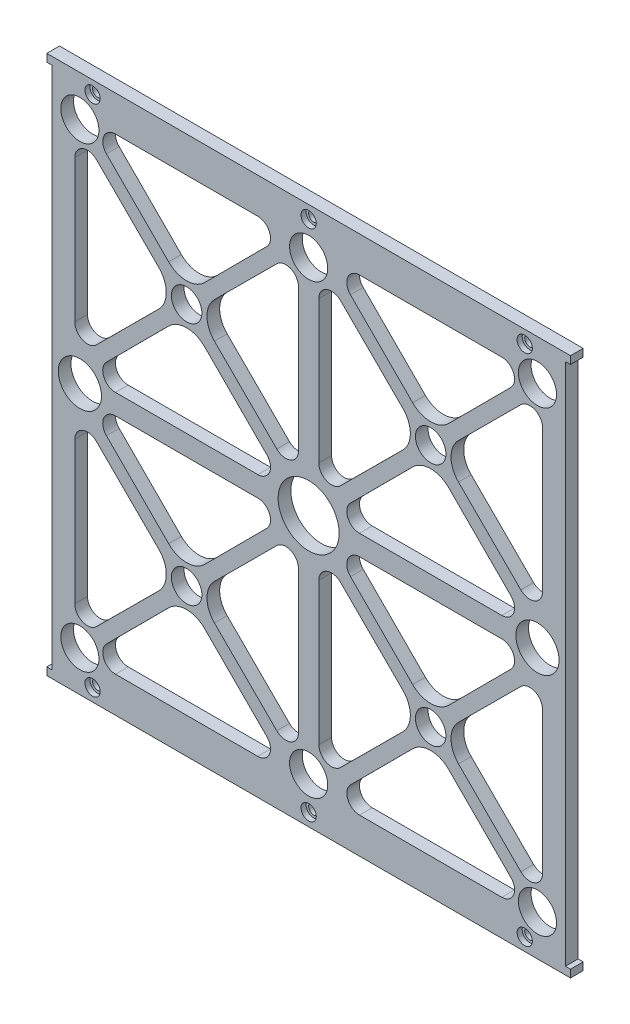
SolidWorks part; units mm, degrees
ref_plane "Přední rovina" through (0, 0, 0) normal (0, 0, 1) x (1, 0, 0)
ref_plane "Horní rovina" through (0, 0, 0) normal (0, 1, 0) x (1, 0, 0)
ref_plane "Pravá rovina" through (0, 0, 0) normal (1, 0, 0) x (0, 0, -1)
sketch "Skica1" plane through (0, 0, 0) normal (0, 0, 1) x (1, 0, 0)
  line L0 (0, 0) -> (103, 0) construction
  line L1 (0, 0) -> (0, 106) construction
  line L7 (103, 0) -> (103, 106) construction
  line L19 (-103, 106) -> (103, 106)
  line L20 (103, 106) -> (103, 103)
  line L21 (103, 103) -> (101, 103)
  line L22 (101, 103) -> (101, -103)
  line L23 (103, -103) -> (101, -103)
  line L24 (103, -106) -> (103, -103)
  line L25 (-103, -106) -> (103, -106)
  line L26 (-103, 103) -> (-101, 103)
  line L27 (-103, 106) -> (-103, 103)
  line L28 (-101, 103) -> (-101, -103)
  line L29 (-103, -103) -> (-101, -103)
  line L30 (-103, -106) -> (-103, -103)
  dimension "D1" = 212
  dimension "D2" = 206
  dimension "D3" = 3
  dimension "D4" = 2
extrude "Přidat vysunutím1" add sketch "Skica1" along normal blind 5 contours L27 L26 L28 L29 L30 L25 L24 L23 L22 L21 L20 L19
sketch "Skica2" plane through (0, 0, 5) normal (0, 0, 1) x (1, 0, 0)
  line L0 (0, 0) -> (0, 101) construction
  line L1 (0, 101) -> (-85, 101) construction
  line L2 (0, 0) -> (-79.6692, 0) construction
  circle A6 centre (-85, 101) radius 2
  circle A7 centre (0, 101) radius 2
  circle A8 centre (85, 101) radius 2
  circle A9 centre (-85, -101) radius 2
  circle A10 centre (0, -101) radius 2
  circle A11 centre (85, -101) radius 2
  dimension "D1" = 85
  dimension "D4" = 3
  dimension "D5" = 85
  dimension "D3" = 4
  dimension "D2" = 101
extrude "Odebrat vysunutím1" cut sketch "Skica2" against normal through all
sketch "Skica4" plane through (0, 0, 5) normal (0, 0, 1) x (1, 0, 0)
  line L0 (0, 0) -> (48, 0) construction
  line L1 (48, 0) -> (48, 48) construction
  line L2 (48, 48) -> (48, 66) construction
  line L3 (48, 66) -> (48, 87) construction
  line L4 (48, 87) -> (20, 87) construction
  line L5 (40.9187, 58.9392) -> (16.4593, 83.4696)
  line L6 (55.0813, 58.9392) -> (79.5407, 83.4696)
  line L7 (20, 92) -> (76, 92)
  line L8 (48, 48) -> (-1, 97) construction
  line L10 (37.0608, 55.0813) -> (12.5304, 79.5407)
  line L11 (4, 76) -> (4, 20)
  line L12 (37.0608, 40.9187) -> (12.5304, 16.4593)
  line L13 (58.9392, 40.9187) -> (83.4696, 16.4593)
  line L14 (92, 76) -> (92, 20)
  line L15 (58.9392, 55.0813) -> (83.4696, 79.5407)
  line L16 (48, 48) -> (66, 48) construction
  line L20 (40.9187, 37.0608) -> (16.4593, 12.5304)
  line L21 (20, 4) -> (76, 4)
  line L22 (55.0813, 37.0608) -> (79.5407, 12.5304)
  line L23 (0, 0) -> (0, 95) construction
  line L24 (-40.9187, 58.9392) -> (-16.4593, 83.4696)
  line L25 (-20, 92) -> (-76, 92)
  line L26 (-55.0813, 58.9392) -> (-79.5407, 83.4696)
  line L27 (-58.9392, 55.0813) -> (-83.4696, 79.5407)
  line L28 (-92, 76) -> (-92, 20)
  line L29 (-58.9392, 40.9187) -> (-83.4696, 16.4593)
  line L30 (-55.0813, 37.0608) -> (-79.5407, 12.5304)
  line L31 (-20, 4) -> (-76, 4)
  line L32 (-40.9187, 37.0608) -> (-16.4593, 12.5304)
  line L33 (-37.0608, 40.9187) -> (-12.5304, 16.4593)
  line L34 (-4, 76) -> (-4, 20)
  line L35 (-37.0608, 55.0813) -> (-12.5304, 79.5407)
  line L36 (40.9187, -58.9392) -> (16.4593, -83.4696)
  line L37 (20, -92) -> (76, -92)
  line L38 (55.0813, -58.9392) -> (79.5407, -83.4696)
  line L39 (58.9392, -55.0813) -> (83.4696, -79.5407)
  line L40 (92, -76) -> (92, -20)
  line L41 (58.9392, -40.9187) -> (83.4696, -16.4593)
  line L42 (55.0813, -37.0608) -> (79.5407, -12.5304)
  line L43 (20, -4) -> (76, -4)
  line L44 (40.9187, -37.0608) -> (16.4593, -12.5304)
  line L45 (37.0608, -40.9187) -> (12.5304, -16.4593)
  line L46 (4, -76) -> (4, -20)
  line L47 (37.0608, -55.0813) -> (12.5304, -79.5407)
  line L48 (-37.0608, -55.0813) -> (-12.5304, -79.5407)
  line L49 (-4, -76) -> (-4, -20)
  line L50 (-37.0608, -40.9187) -> (-12.5304, -16.4593)
  line L51 (-55.0813, -58.9392) -> (-79.5407, -83.4696)
  line L52 (-20, -92) -> (-76, -92)
  line L53 (-40.9187, -58.9392) -> (-16.4593, -83.4696)
  line L54 (-58.9392, -40.9187) -> (-83.4696, -16.4593)
  line L55 (-92, -76) -> (-92, -20)
  line L56 (-58.9392, -55.0813) -> (-83.4696, -79.5407)
  line L57 (-40.9187, -37.0608) -> (-16.4593, -12.5304)
  line L58 (-20, -4) -> (-76, -4)
  line L59 (-55.0813, -37.0608) -> (-79.5407, -12.5304)
  circle A0 centre (48, 48) radius 6
  arc A1 (40.9187, 58.9392) -> (55.0813, 58.9392) centre (48, 66) ccw
  arc A2 (20, 92) -> (16.4593, 83.4696) centre (20, 87) ccw
  arc A3 (76, 92) -> (79.5407, 83.4696) centre (76, 87) cw
  arc A4 (4, 76) -> (12.5304, 79.5407) centre (9, 76) cw
  arc A5 (4, 20) -> (12.5304, 16.4593) centre (9, 20) ccw
  arc A6 (37.0608, 55.0813) -> (37.0608, 40.9187) centre (30, 48) cw
  arc A7 (58.9392, 55.0813) -> (58.9392, 40.9187) centre (66, 48) ccw
  arc A8 (92, 20) -> (83.4696, 16.4593) centre (87, 20) cw
  arc A9 (92, 76) -> (83.4696, 79.5407) centre (87, 76) ccw
  arc A10 (20, 4) -> (16.4593, 12.5304) centre (20, 9) cw
  arc A11 (76, 4) -> (79.5407, 12.5304) centre (76, 9) ccw
  arc A12 (40.9187, 37.0608) -> (55.0813, 37.0608) centre (48, 30) cw
  arc A13 (-20, 92) -> (-16.4593, 83.4696) centre (-20, 87) cw
  arc A14 (-76, 92) -> (-79.5407, 83.4696) centre (-76, 87) ccw
  arc A15 (-40.9187, 58.9392) -> (-55.0813, 58.9392) centre (-48, 66) cw
  circle A16 centre (-48, 48) radius 6
  arc A17 (-92, 76) -> (-83.4696, 79.5407) centre (-87, 76) cw
  arc A18 (-92, 20) -> (-83.4696, 16.4593) centre (-87, 20) ccw
  arc A19 (-58.9392, 55.0813) -> (-58.9392, 40.9187) centre (-66, 48) cw
  arc A20 (-40.9187, 37.0608) -> (-55.0813, 37.0608) centre (-48, 30) ccw
  arc A21 (-76, 4) -> (-79.5407, 12.5304) centre (-76, 9) cw
  arc A22 (-20, 4) -> (-16.4593, 12.5304) centre (-20, 9) ccw
  arc A23 (-37.0608, 55.0813) -> (-37.0608, 40.9187) centre (-30, 48) ccw
  arc A24 (-4, 20) -> (-12.5304, 16.4593) centre (-9, 20) cw
  arc A25 (-4, 76) -> (-12.5304, 79.5407) centre (-9, 76) ccw
  arc A26 (20, -92) -> (16.4593, -83.4696) centre (20, -87) cw
  arc A27 (76, -92) -> (79.5407, -83.4696) centre (76, -87) ccw
  arc A28 (40.9187, -58.9392) -> (55.0813, -58.9392) centre (48, -66) cw
  circle A29 centre (48, -48) radius 6
  arc A30 (92, -76) -> (83.4696, -79.5407) centre (87, -76) cw
  arc A31 (92, -20) -> (83.4696, -16.4593) centre (87, -20) ccw
  arc A32 (58.9392, -55.0813) -> (58.9392, -40.9187) centre (66, -48) cw
  arc A33 (40.9187, -37.0608) -> (55.0813, -37.0608) centre (48, -30) ccw
  arc A34 (76, -4) -> (79.5407, -12.5304) centre (76, -9) cw
  arc A35 (20, -4) -> (16.4593, -12.5304) centre (20, -9) ccw
  arc A36 (37.0608, -55.0813) -> (37.0608, -40.9187) centre (30, -48) ccw
  arc A37 (4, -20) -> (12.5304, -16.4593) centre (9, -20) cw
  arc A38 (4, -76) -> (12.5304, -79.5407) centre (9, -76) ccw
  arc A39 (-4, -76) -> (-12.5304, -79.5407) centre (-9, -76) cw
  arc A40 (-4, -20) -> (-12.5304, -16.4593) centre (-9, -20) ccw
  arc A41 (-37.0608, -55.0813) -> (-37.0608, -40.9187) centre (-30, -48) cw
  arc A42 (-40.9187, -58.9392) -> (-55.0813, -58.9392) centre (-48, -66) ccw
  arc A43 (-76, -92) -> (-79.5407, -83.4696) centre (-76, -87) cw
  arc A44 (-20, -92) -> (-16.4593, -83.4696) centre (-20, -87) ccw
  circle A45 centre (-48, -48) radius 6
  arc A46 (-58.9392, -55.0813) -> (-58.9392, -40.9187) centre (-66, -48) ccw
  arc A47 (-92, -20) -> (-83.4696, -16.4593) centre (-87, -20) cw
  arc A48 (-92, -76) -> (-83.4696, -79.5407) centre (-87, -76) ccw
  arc A49 (-20, -4) -> (-16.4593, -12.5304) centre (-20, -9) cw
  arc A50 (-76, -4) -> (-79.5407, -12.5304) centre (-76, -9) ccw
  arc A51 (-40.9187, -37.0608) -> (-55.0813, -37.0608) centre (-48, -30) cw
  dimension "D3" = 12
  dimension "D4" = 20
  dimension "D7" = 10
  dimension "D9" = 135
  dimension "D1" = 48
  dimension "D2" = 48
  dimension "D5" = 18
  dimension "D6" = 21
  dimension "D8" = 56
extrude "Odebrat vysunutím3" cut sketch "Skica4" against normal blind 10
sketch "Skica5" plane through (0, 0, 5) normal (0, 0, 1) x (1, 0, 0)
  line L0 (0, 0) -> (101, 0) construction
  line L1 (101, 103) -> (101, -103) construction
  circle A0 centre (-85, 101) radius 3
  circle A1 centre (0, 101) radius 3
  circle A2 centre (85, 101) radius 3
  circle A3 centre (-85, -101) radius 3
  circle A4 centre (0, -101) radius 3
  circle A5 centre (85, -101) radius 3
  dimension "D1" = 6
  dimension "D2" = 3
  dimension "D3" = 85
extrude "Odebrat vysunutím4" cut sketch "Skica5" against normal blind 2
sketch "Skica6" plane through (0, 0, 5) normal (0, 0, 1) x (1, 0, 0)
  line L0 (0, 0) -> (-90, 0) construction
  line L1 (0, 0) -> (0, 88) construction
  line L2 (-90, 0) -> (-90, 90) construction
  line L3 (-90, -90) -> (-90, 0) construction
  circle A0 centre (0, 0) radius 12
  circle A1 centre (-90, 0) radius 8.5
  circle A2 centre (90, 0) radius 8.5
  circle A3 centre (-90, 90) radius 7.5
  circle A4 centre (90, 90) radius 7.5
  circle A5 centre (90, -90) radius 7.5
  circle A6 centre (-90, -90) radius 7.5
  circle A7 centre (0, 88) radius 7.5
  circle A8 centre (0, -88) radius 7.5
  dimension "D1" = 24
  dimension "D3" = 17
  dimension "D5" = 15
  dimension "D6" = 2
  dimension "D11" = 15
  dimension "D2" = 90
  dimension "D4" = 90
  dimension "D8" = 180
  dimension "D9" = 180
  dimension "D10" = 88
  dimension "D7" = 2
extrude "Odebrat vysunutím5" cut sketch "Skica6" against normal through all
